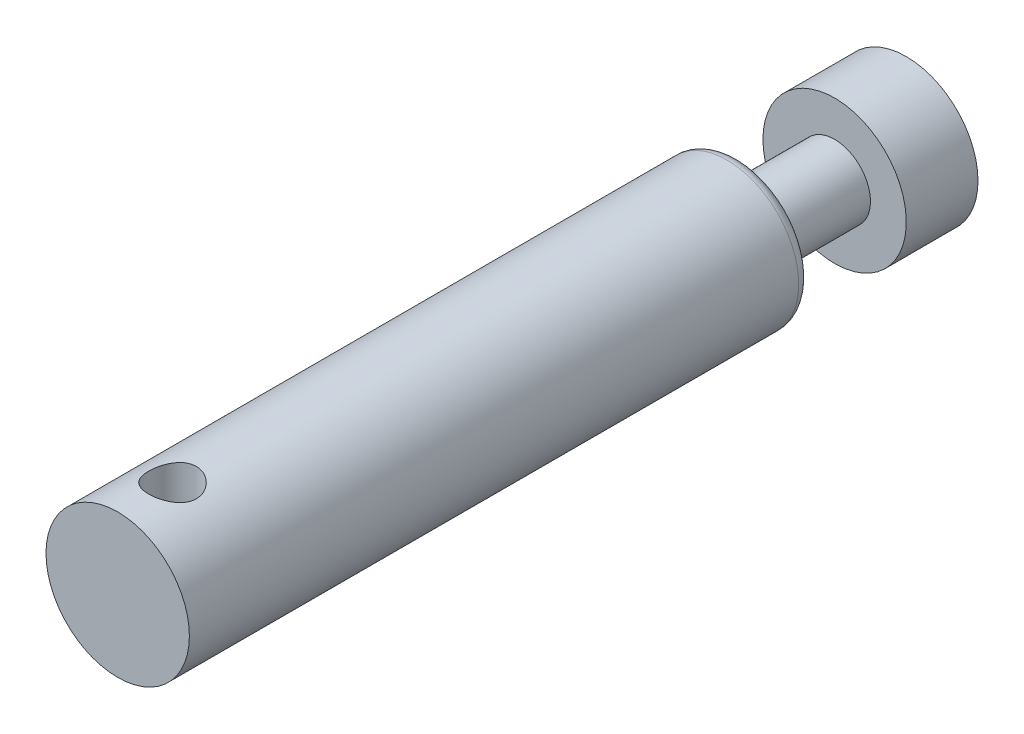
SolidWorks part; units mm, degrees
ref_plane "Front Plane" through (0, 0, 0) normal (0, 0, 1) x (1, 0, 0)
ref_plane "Top Plane" through (0, 0, 0) normal (0, 1, 0) x (1, 0, 0)
ref_plane "Right Plane" through (0, 0, 0) normal (1, 0, 0) x (0, 0, -1)
sketch "Sketch1" plane through (0, 0, 0) normal (0, 0, 1) x (1, 0, 0)
  circle A0 centre (0, 0) radius 3
extrude "Boss-Extrude1" add sketch "Sketch1" along normal blind 33
sketch "Sketch2" plane through (0, 0, 0) normal (0, 1, 0) x (1, 0, 0)
  line L0 (3, -3) -> (1.5, -3)
  line L1 (3, -33) -> (3, 0) construction
  line L2 (1.5, -3) -> (1.5, -7)
  line L3 (1.5, -7) -> (3, -7)
  line L4 (3, 0) -> (-3, 0) construction
  line L5 (0, 0) -> (0, -8.5893) construction
  line L6 (3, -3) -> (3, -7)
  dimension "D1" = 3
  dimension "D2" = 4
  dimension "D3" = 1.5
revolve "Cut-Revolve1" cut sketch "Sketch2" angle 360 about L5
fillet "Fillet2" radius 0.5 1 edges at (-3, 0, 7)
sketch "Sketch3" plane through (0, 0, 0) normal (0, 1, 0) x (1, 0, 0)
  circle A0 centre (0, -30.7066) radius 1
  point P2 (0, -30.7066)
extrude "Cut-Extrude2" cut sketch "Sketch3" against normal through all both and the other way through all
